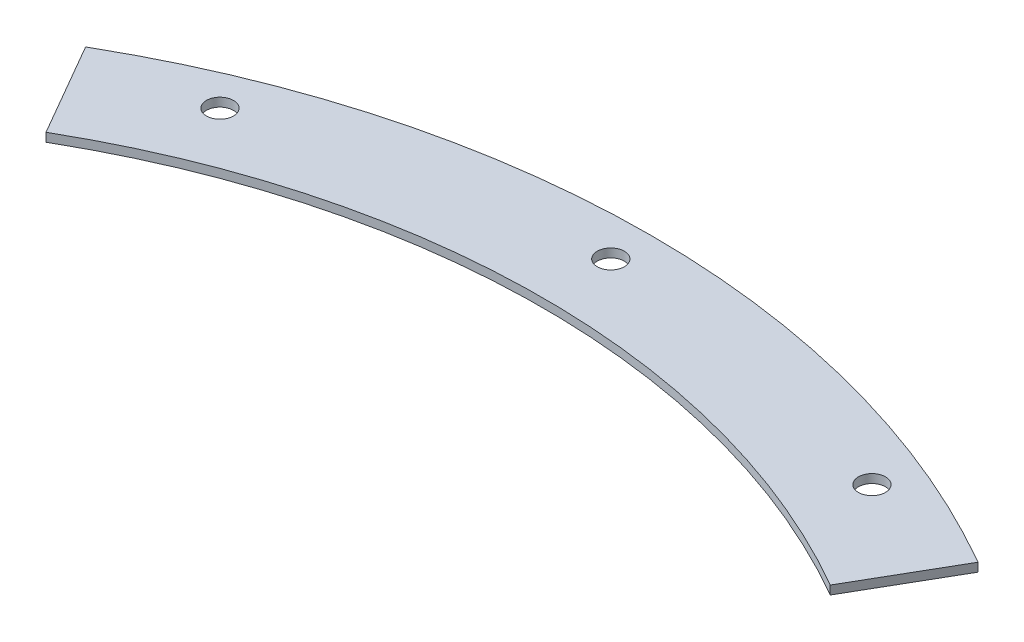
SolidWorks part; units mm, degrees
material "A-Glass Fiber"
ref_plane "Front Plane" through (0, 0, 0) normal (0, 0, 1) x (1, 0, 0)
ref_plane "Top Plane" through (0, 0, 0) normal (0, 1, 0) x (1, 0, 0)
ref_plane "Right Plane" through (0, 0, 0) normal (1, 0, 0) x (0, 0, -1)
sketch "Sketch1" plane through (0, 0, 0) normal (0, 1, 0) x (1, 0, 0)
  line L0 (-72.5, 125.5737) -> (-82.5, 142.8942)
  line L1 (72.5, 125.5737) -> (82.5, 142.8942)
  arc A0 (-72.5, 125.5737) -> (72.5, 125.5737) centre (0, 0) cw
  arc A1 (-82.5, 142.8942) -> (82.5, 142.8942) centre (0, 0) cw
  point P7 (0, 145)
  dimension "D1" = 145
  dimension "D2" = 20
  dimension "D3" = 60
extrude "Boss-Extrude1" add sketch "Sketch1" along normal blind 1.6
sketch "Sketch2" plane through (0, 0, 0) normal (0, -1, 0) x (1, 0, 0)
  line L2 (0, 0) -> (0, -157.5) construction
  line L3 (60.2726, -145.511) -> (0, 0) construction
  line L4 (-60.2726, -145.511) -> (0, 0) construction
  circle A0 centre (-60.2726, -145.511) radius 2.5
  arc A1 (-82.5, -142.8942) -> (82.5, -142.8942) centre (0, 0) ccw construction
  circle A2 centre (0, -157.5) radius 2.5
  circle A3 centre (60.2726, -145.511) radius 2.5
  circle A4 centre (0, 0) radius 157.5 construction
  point P5 (0, 0)
  point P6 (0, -165)
  point P8 (0, 0)
  point P13 (-0.1902, 0.0342)
  dimension "D1" = 5
  dimension "D4" = 315
  dimension "D2" = 22.5
  dimension "D3" = 22.5
extrude "Cut-Extrude1" cut sketch "Sketch2" against normal blind 10 contours A0 | A2 | A3
